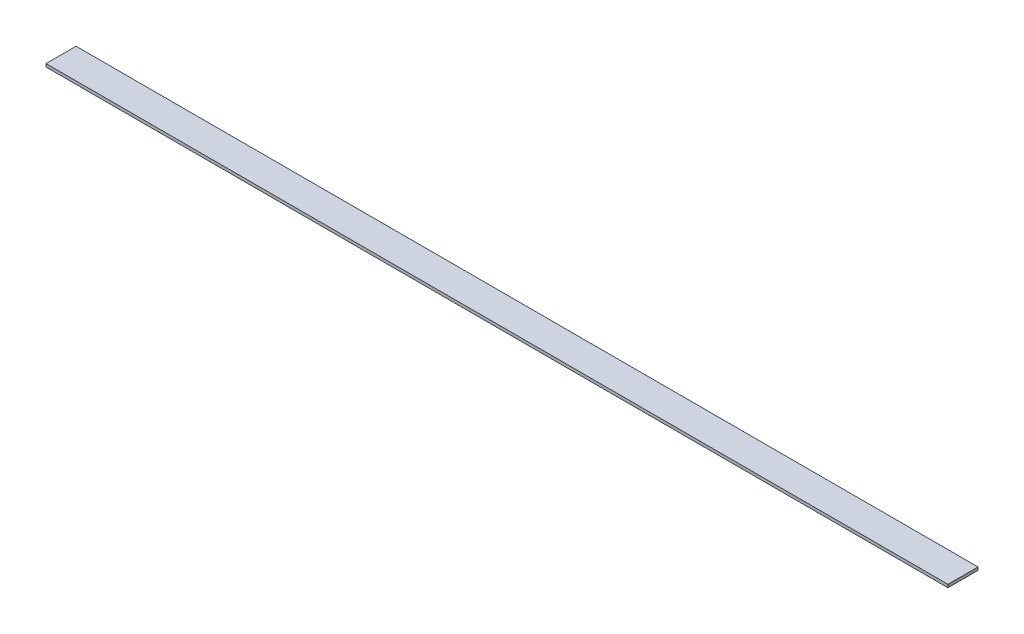
SolidWorks part; units mm, degrees
ref_plane "Front Plane" through (0, 0, 0) normal (0, 0, 1) x (1, 0, 0)
ref_plane "Top Plane" through (0, 0, 0) normal (0, 1, 0) x (1, 0, 0)
ref_plane "Right Plane" through (0, 0, 0) normal (1, 0, 0) x (0, 0, -1)
sketch "Sketch1" plane through (0, 0, 0) normal (0, 0, 1) x (1, 0, 0)
  line L1 (-150, -0.5) -> (150, -0.5)
  line L2 (-150, -0.5) -> (-150, 0.5)
  line L3 (-150, 0.5) -> (150, 0.5)
  line L4 (150, -0.5) -> (150, 0.5)
  line L5 (-150, -0.5) -> (150, 0.5) construction
  line L6 (-150, 0.5) -> (150, -0.5) construction
  point P0 (0, 0)
  dimension "D1" = 300
  dimension "D2" = 1
extrude "Boss-Extrude1" add sketch "Sketch1" along normal blind 10
